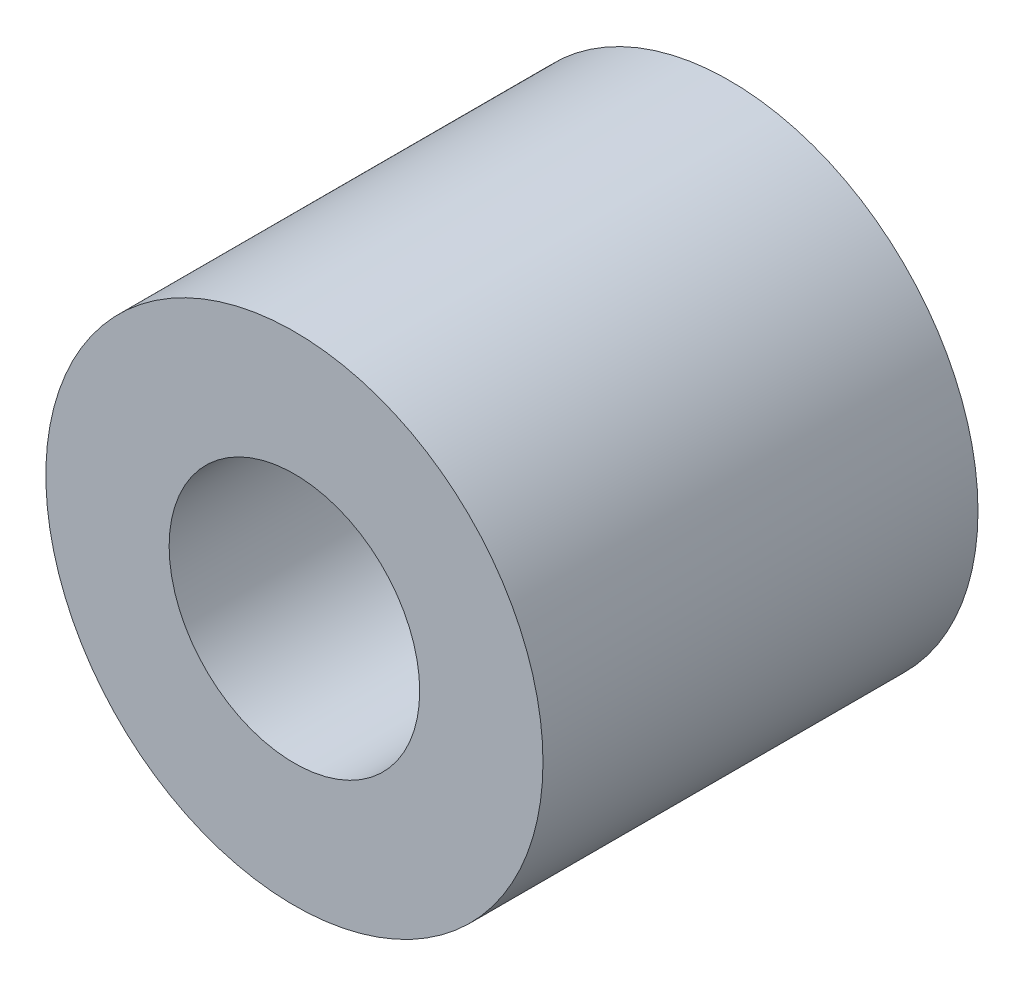
SolidWorks part; units mm, degrees
ref_plane "Front Plane" through (0, 0, 0) normal (0, 0, 1) x (1, 0, 0)
ref_plane "Top Plane" through (0, 0, 0) normal (0, 1, 0) x (1, 0, 0)
ref_plane "Right Plane" through (0, 0, 0) normal (1, 0, 0) x (0, 0, -1)
sketch "Sketch1" plane through (0, 0, 0) normal (0, 0, 1) x (1, 0, 0)
  circle A0 centre (0, 0) radius 6.35
  circle A1 centre (0, 0) radius 3.2004
  dimension "OD" = 12.7
  dimension "ID" = 6.4008
extrude "Extrude1" add sketch "Sketch1" along normal mid plane 11.1125
sketch "Sketch2" plane through (0, 0, 0) normal (1, 0, 0) x (0, 0, -1)
  line L0 (-5.5562, -3.2004) -> (5.5562, -3.2004) construction
  line L3 (5.5562, 3.2004) -> (-5.5562, 3.2004) construction
  line L5 (-5.5562, -3.2004) -> (5.5562, -3.2004)
  line L6 (5.5562, 3.2004) -> (-5.5562, 3.2004)
sketch "Sketch4" plane through (0, 0, 5.5562) normal (0, 0, 1) x (1, 0, 0)
  line L0 (0, 0) -> (-2.263, 2.263)
  line L1 (0, -5.2388) -> (0, 5.2388) construction
  circle A0 centre (0, 0) radius 3.2004 construction
  dimension "D1" = 45
